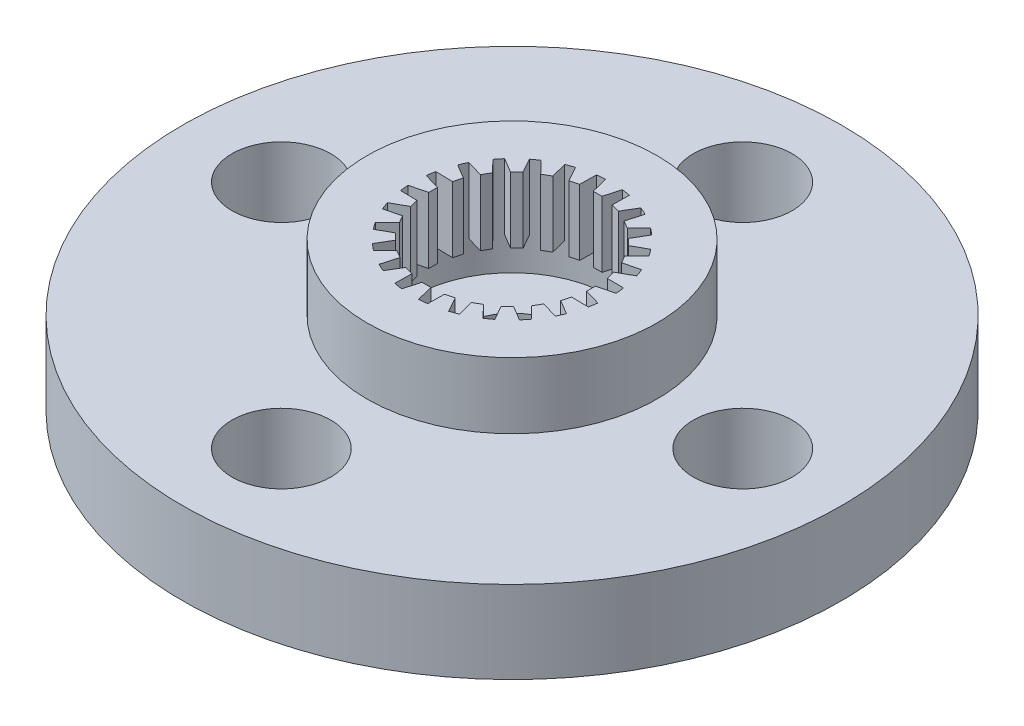
SolidWorks part; units mm, degrees
ref_plane "前视基准面" through (0, 0, 0) normal (0, 0, 1) x (1, 0, 0)
ref_plane "上视基准面" through (0, 0, 0) normal (0, 1, 0) x (1, 0, 0)
ref_plane "右视基准面" through (0, 0, 0) normal (1, 0, 0) x (0, 0, -1)
sketch "草图1" plane through (0, 0, 0) normal (0, 0, 1) x (1, 0, 0)
  line L0 (10, 2.5) -> (0, 2.5)
  line L1 (0, 2.5) -> (0, 0)
  line L2 (0, 0) -> (10, 0)
  line L3 (10, 0) -> (10, 2.5)
  line L4 (0, 2.5) -> (0, 0) construction
revolve "旋转1" add sketch "草图1" angle 360 about L4
sketch "草图2" plane through (0, 2.5, 0) normal (0, 1, 0) x (-1, 0, 0)
  circle A0 centre (0, 0) radius 3
extrude "切除-拉伸1" cut sketch "草图2" against normal blind 1
sketch "草图3" plane through (0, 2.5, 0) normal (0, 1, 0) x (-1, 0, 0)
  line L0 (-1.1293, -2.7793) -> (-0.9121, -2.415)
  line L1 (-0.9121, -2.415) -> (-0.6148, -2.4191)
  line L2 (-0.6148, -2.4191) -> (-0.622, -2.9348)
  line L3 (-0.3715, -2.9769) -> (-0.2354, -2.4958)
  line L4 (-0.2354, -2.4958) -> (0.0323, -2.4958)
  line L5 (0.0323, -2.4958) -> (0.1588, -2.9958)
  line L6 (0.4116, -2.9716) -> (0.4186, -2.4717)
  line L7 (0.4186, -2.4717) -> (0.7182, -2.4758)
  line L8 (0.7182, -2.4758) -> (0.9288, -2.8526)
  line L9 (1.1667, -2.7638) -> (1.0441, -2.2791)
  line L10 (1.0441, -2.2791) -> (1.2758, -2.1453)
  line L11 (1.2758, -2.1453) -> (1.6354, -2.515)
  line L12 (1.8423, -2.3677) -> (1.5984, -1.9312)
  line L13 (1.5984, -1.9312) -> (1.7876, -1.742)
  line L14 (1.7876, -1.742) -> (2.2307, -2.006)
  line L15 (2.3923, -1.8102) -> (2.0437, -1.4517)
  line L16 (2.0437, -1.4517) -> (2.1776, -1.2199)
  line L17 (2.1776, -1.2199) -> (2.6738, -1.3604)
  line L18 (2.7793, -1.1293) -> (2.415, -0.9121)
  line L19 (2.415, -0.9121) -> (2.4191, -0.6148)
  line L20 (2.4191, -0.6148) -> (2.9348, -0.622)
  line L21 (2.9769, -0.3715) -> (2.4958, -0.2354)
  line L22 (2.4958, -0.2354) -> (2.4958, 0.0323)
  line L23 (2.4958, 0.0323) -> (2.9958, 0.1588)
  line L24 (2.9716, 0.4116) -> (2.4717, 0.4186)
  line L25 (2.4717, 0.4186) -> (2.4758, 0.7182)
  line L26 (2.4758, 0.7182) -> (2.8526, 0.9288)
  line L27 (2.7638, 1.1667) -> (2.2791, 1.0441)
  line L28 (2.2791, 1.0441) -> (2.1453, 1.2758)
  line L29 (2.1453, 1.2758) -> (2.515, 1.6354)
  line L30 (2.3677, 1.8423) -> (1.9312, 1.5984)
  line L31 (1.9312, 1.5984) -> (1.742, 1.7876)
  line L32 (1.742, 1.7876) -> (2.006, 2.2307)
  line L33 (1.8102, 2.3923) -> (1.4517, 2.0437)
  line L34 (1.4517, 2.0437) -> (1.2199, 2.1776)
  line L35 (1.2199, 2.1776) -> (1.3604, 2.6738)
  line L36 (1.1293, 2.7793) -> (0.9121, 2.415)
  line L37 (0.9121, 2.415) -> (0.6148, 2.4191)
  line L38 (0.6148, 2.4191) -> (0.622, 2.9348)
  line L39 (0.3715, 2.9769) -> (0.2354, 2.4958)
  line L40 (0.2354, 2.4958) -> (-0.0323, 2.4958)
  line L41 (-0.0323, 2.4958) -> (-0.1588, 2.9958)
  line L42 (-0.4116, 2.9716) -> (-0.4186, 2.4717)
  line L43 (-0.4186, 2.4717) -> (-0.7182, 2.4758)
  line L44 (-0.7182, 2.4758) -> (-0.9288, 2.8526)
  line L45 (-1.1667, 2.7638) -> (-1.0441, 2.2791)
  line L46 (-1.0441, 2.2791) -> (-1.2758, 2.1453)
  line L47 (-1.2758, 2.1453) -> (-1.6354, 2.515)
  line L48 (-1.8423, 2.3677) -> (-1.5984, 1.9312)
  line L49 (-1.5984, 1.9312) -> (-1.7876, 1.742)
  line L50 (-1.7876, 1.742) -> (-2.2307, 2.006)
  line L51 (-2.3923, 1.8102) -> (-2.0437, 1.4517)
  line L52 (-2.0437, 1.4517) -> (-2.1776, 1.2199)
  line L53 (-2.1776, 1.2199) -> (-2.6738, 1.3604)
  line L54 (-2.7793, 1.1293) -> (-2.415, 0.9121)
  line L55 (-2.415, 0.9121) -> (-2.4191, 0.6148)
  line L56 (-2.4191, 0.6148) -> (-2.9348, 0.622)
  line L57 (-2.9769, 0.3715) -> (-2.4958, 0.2354)
  line L58 (-2.4958, 0.2354) -> (-2.4958, -0.0323)
  line L59 (-2.4958, -0.0323) -> (-2.9958, -0.1588)
  line L60 (-2.9716, -0.4116) -> (-2.4717, -0.4186)
  line L61 (-2.4717, -0.4186) -> (-2.4758, -0.7182)
  line L62 (-2.4758, -0.7182) -> (-2.8526, -0.9288)
  line L63 (-2.7638, -1.1667) -> (-2.2791, -1.0441)
  line L64 (-2.2791, -1.0441) -> (-2.1453, -1.2758)
  line L65 (-2.1453, -1.2758) -> (-2.515, -1.6354)
  line L66 (-2.3677, -1.8423) -> (-1.9312, -1.5984)
  line L67 (-1.9312, -1.5984) -> (-1.742, -1.7876)
  line L68 (-1.742, -1.7876) -> (-2.006, -2.2307)
  line L69 (-1.8102, -2.3923) -> (-1.4517, -2.0437)
  line L70 (-1.4517, -2.0437) -> (-1.2199, -2.1776)
  line L71 (-1.2199, -2.1776) -> (-1.3604, -2.6738)
  circle A0 centre (0, 0) radius 4.4
  arc A1 (-1.3604, -2.6738) -> (-1.1293, -2.7793) centre (0, 0) ccw
  arc A2 (-0.622, -2.9348) -> (-0.3715, -2.9769) centre (0, 0) ccw
  arc A3 (0.1588, -2.9958) -> (0.4116, -2.9716) centre (0, 0) ccw
  arc A4 (0.9288, -2.8526) -> (1.1667, -2.7638) centre (0, 0) ccw
  arc A5 (1.6354, -2.515) -> (1.8423, -2.3677) centre (0, 0) ccw
  arc A6 (2.2307, -2.006) -> (2.3923, -1.8102) centre (0, 0) ccw
  arc A7 (2.6738, -1.3604) -> (2.7793, -1.1293) centre (0, 0) ccw
  arc A8 (2.9348, -0.622) -> (2.9769, -0.3715) centre (0, 0) ccw
  arc A9 (2.9958, 0.1588) -> (2.9716, 0.4116) centre (0, 0) ccw
  arc A10 (2.8526, 0.9288) -> (2.7638, 1.1667) centre (0, 0) ccw
  arc A11 (2.515, 1.6354) -> (2.3677, 1.8423) centre (0, 0) ccw
  arc A12 (2.006, 2.2307) -> (1.8102, 2.3923) centre (0, 0) ccw
  arc A13 (1.3604, 2.6738) -> (1.1293, 2.7793) centre (0, 0) ccw
  arc A14 (0.622, 2.9348) -> (0.3715, 2.9769) centre (0, 0) ccw
  arc A15 (-0.1588, 2.9958) -> (-0.4116, 2.9716) centre (0, 0) ccw
  arc A16 (-0.9288, 2.8526) -> (-1.1667, 2.7638) centre (0, 0) ccw
  arc A17 (-1.6354, 2.515) -> (-1.8423, 2.3677) centre (0, 0) ccw
  arc A18 (-2.2307, 2.006) -> (-2.3923, 1.8102) centre (0, 0) ccw
  arc A19 (-2.6738, 1.3604) -> (-2.7793, 1.1293) centre (0, 0) ccw
  arc A20 (-2.9348, 0.622) -> (-2.9769, 0.3715) centre (0, 0) ccw
  arc A21 (-2.9958, -0.1588) -> (-2.9716, -0.4116) centre (0, 0) ccw
  arc A22 (-2.8526, -0.9288) -> (-2.7638, -1.1667) centre (0, 0) ccw
  arc A23 (-2.515, -1.6354) -> (-2.3677, -1.8423) centre (0, 0) ccw
  arc A24 (-2.006, -2.2307) -> (-1.8102, -2.3923) centre (0, 0) ccw
extrude "凸台-拉伸1" add sketch "草图3" along normal blind 2
draft "拔模1" type of draft neutral plane draft angle 15.797 faces to draft 1 face at (-0.5684, 3.5, -2.4738) neutral plane through (-0.4116, 4.5, -2.9716) neutral plane normal (0.9999, 0, 0.0139) parameters "D1"=15.797
draft "拔模2" type of draft neutral plane draft angle 14.203 faces to draft 1 face at (-2.417, 3.5, -0.7635) neutral plane through (-2.4191, 4.5, -0.6148) neutral plane normal (-0.0139, 0, 0.9999) parameters "D1"=14.203
draft "拔模3" type of draft neutral plane draft angle 15.797 faces to draft 1 face at (-2.4738, 3.5, 0.5684) neutral plane through (-2.9716, 4.5, 0.4116) neutral plane normal (0.0139, 0, -0.9999) parameters "D1"=15.797
draft "拔模4" type of draft neutral plane draft angle 14.203 faces to draft 1 face at (-0.7635, 3.5, 2.417) neutral plane through (-0.6148, 4.5, 2.4191) neutral plane normal (0.9999, 0, 0.0139) parameters "D1"=14.203
draft "拔模5" type of draft neutral plane draft angle 15.797 faces to draft 1 face at (0.5684, 3.5, 2.4738) neutral plane through (0.4116, 4.5, 2.9716) neutral plane normal (-0.9999, 0, -0.0139) parameters "D1"=15.797
draft "拔模6" type of draft neutral plane draft angle 14.203 faces to draft 1 face at (2.417, 3.5, 0.7635) neutral plane through (2.4191, 4.5, 0.6148) neutral plane normal (0.0139, 0, -0.9999) parameters "D1"=14.203
draft "拔模7" type of draft neutral plane draft angle 15.797 faces to draft 1 face at (2.4738, 3.5, -0.5684) neutral plane through (2.9716, 4.5, -0.4116) neutral plane normal (-0.0139, 0, 0.9999) parameters "D1"=15.797
draft "拔模8" type of draft neutral plane draft angle 14.203 faces to draft 1 face at (0.7635, 3.5, -2.417) neutral plane through (0.6148, 4.5, -2.4191) neutral plane normal (-0.9999, 0, -0.0139) parameters "D1"=14.203
hole_wizard "Ø3.0 (3) 直径孔1" positions "草图5" profile "草图4" hole size "Ø3.0" standard "ANSI Metric"
sketch "草图5" plane through (0, 1.5, 0) normal (0, 1, 0) x (1, 0, 0)
  point P0 (0, 0)
sketch "草图4" plane through (0, 1.5, 0) normal (1, 0, 0) x (0, 0, 1)
  line L0 (0, 0) -> (0, 1.5)
  line L1 (0, 1.5) -> (1.5, 1.5)
  line L2 (1.5, 1.5) -> (1.5, 0)
  line L5 (1.5, 0) -> (0, 0)
  line L11 (0, -6.35) -> (0, 107.95) construction
  dimension "通孔孔直径" = 3
  dimension "通孔孔深度" = 1.5
hole_wizard "Ø3.0 (3) 直径孔2" positions "草图7" profile "草图6" hole size "Ø3.0" standard "ANSI Metric"
sketch "草图7" plane through (0, 2.5, 0) normal (0, 1, 0) x (1, 0, 0)
  point P0 (0, -7)
  point P1 (-7, 0)
  point P2 (7, 0)
  point P3 (0, 7)
sketch "草图6" plane through (0, 2.5, 7) normal (1, 0, 0) x (0, 0, 1)
  line L0 (0, 0) -> (0, 2.5)
  line L1 (0, 2.5) -> (1.5, 2.5)
  line L2 (1.5, 2.5) -> (1.5, 0)
  line L5 (1.5, 0) -> (0, 0)
  line L11 (0, -6.35) -> (0, 107.95) construction
  dimension "通孔孔直径" = 3
  dimension "通孔孔深度" = 2.5
